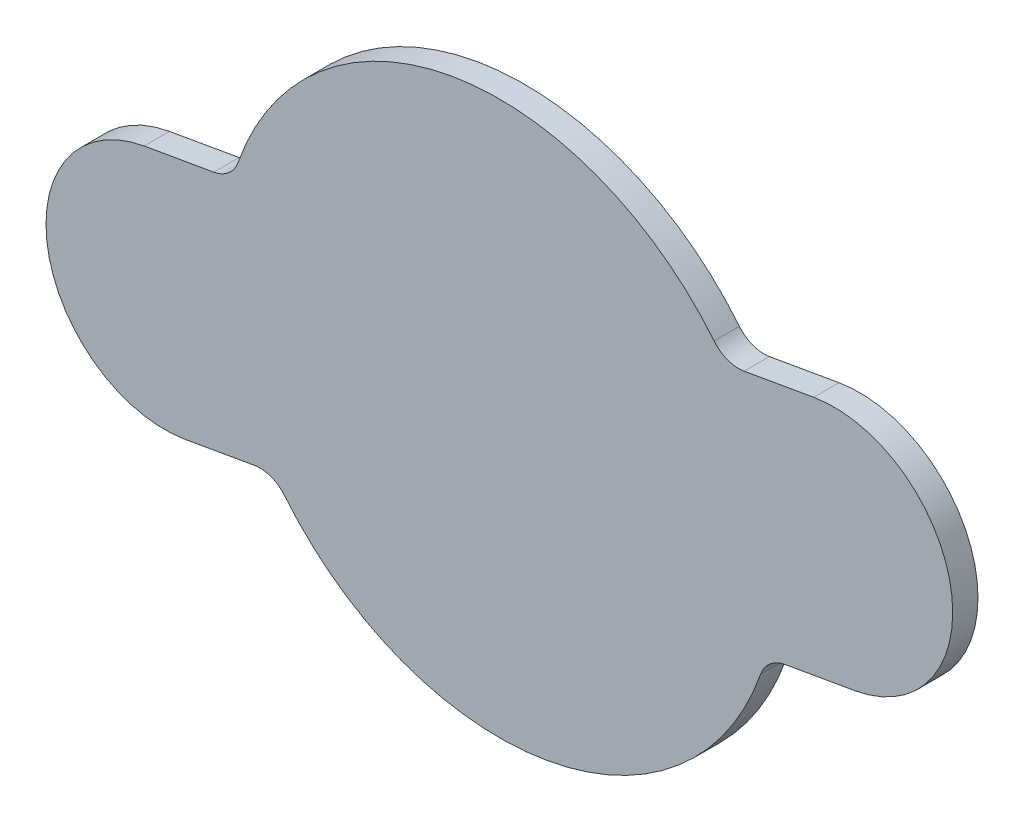
SolidWorks part; units mm, degrees
ref_plane "Front Plane" through (0, 0, 0) normal (0, 0, 1) x (1, 0, 0)
ref_plane "Top Plane" through (0, 0, 0) normal (0, 1, 0) x (1, 0, 0)
ref_plane "Right Plane" through (0, 0, 0) normal (1, 0, 0) x (0, 0, -1)
sketch "Sketch1" plane through (0, 0, 0) normal (0, 0, 1) x (1, 0, 0)
  line L0 (-19.1103, -2.0742) -> (20.0453, 4.7777) construction
  line L1 (-22.0035, 5.0335) -> (-17.5998, 5.8041)
  line L2 (-19.4179, -9.742) -> (-15.0142, -8.9713)
  line L3 (15.9492, 11.6749) -> (20.3529, 12.4455)
  line L4 (18.5347, -3.1006) -> (22.9384, -2.3299)
  arc A0 (14.0519, 12.3841) -> (-16.0561, 7.1155) centre (0.4675, 1.3518) ccw
  arc A1 (-22.0035, 5.0335) -> (-19.4179, -9.742) centre (-20.7107, -2.3542) ccw
  arc A2 (18.5347, -3.1006) -> (16.9911, -4.4119) centre (18.8795, -5.0706) ccw
  arc A3 (-13.117, -9.6806) -> (16.9911, -4.4119) centre (0.4675, 1.3518) ccw
  arc A4 (22.9384, -2.3299) -> (20.3529, 12.4455) centre (21.6457, 5.0578) ccw
  arc A5 (14.0519, 12.3841) -> (15.9492, 11.6749) centre (15.6044, 13.645) ccw
  arc A6 (-13.117, -9.6806) -> (-15.0142, -8.9713) centre (-14.6695, -10.9414) ccw
  arc A7 (-17.5998, 5.8041) -> (-16.0561, 7.1155) centre (-17.9446, 7.7742) ccw
  dimension "D1" = 35
  dimension "D2" = 2
extrude "Boss-Extrude1" add sketch "Sketch1" along normal blind 1.6
